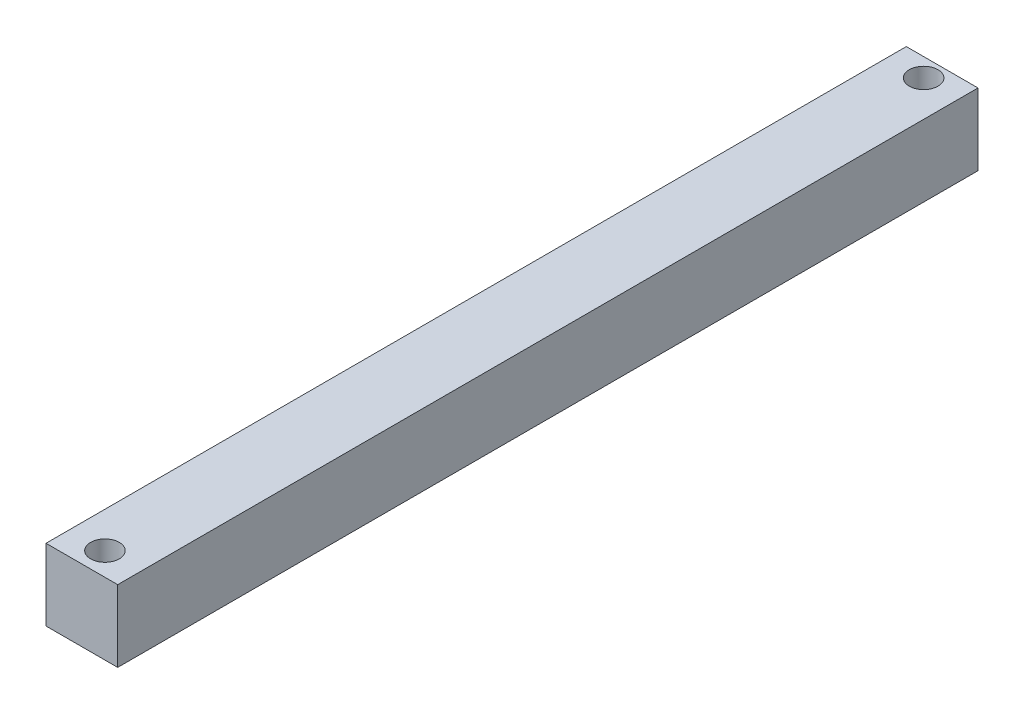
SolidWorks part; units mm, degrees
ref_plane "정면" through (0, 0, 0) normal (0, 0, 1) x (1, 0, 0)
ref_plane "윗면" through (0, 0, 0) normal (0, 1, 0) x (1, 0, 0)
ref_plane "우측면" through (0, 0, 0) normal (1, 0, 0) x (0, 0, -1)
sketch "스케치1" plane through (0, 0, 0) normal (0, 0, 1) x (1, 0, 0)
  line L1 (-14.1299, 10.6681) -> (15.8701, 10.6681)
  line L2 (-14.1299, 10.6681) -> (-14.1299, -19.3319)
  line L3 (-14.1299, -19.3319) -> (15.8701, -19.3319)
  line L4 (15.8701, 10.6681) -> (15.8701, -19.3319)
  dimension "D1" = 30
  dimension "D2" = 30
extrude "보스-돌출1" add sketch "스케치1" along normal blind 360
sketch "스케치2" plane through (0, 10.6681, 0) normal (0, 1, 0) x (1, 0, 0)
  line L0 (-14.1299, -360) -> (-14.1299, 0) construction
  circle A0 centre (0.8701, -7.7487) radius 6
  circle A1 centre (0.8701, -350.3348) radius 6
  dimension "D1" = 12
  dimension "D2" = 12
  dimension "D3" = 15
  dimension "D4" = 15
extrude "컷-돌출1" cut sketch "스케치2" against normal blind 360
